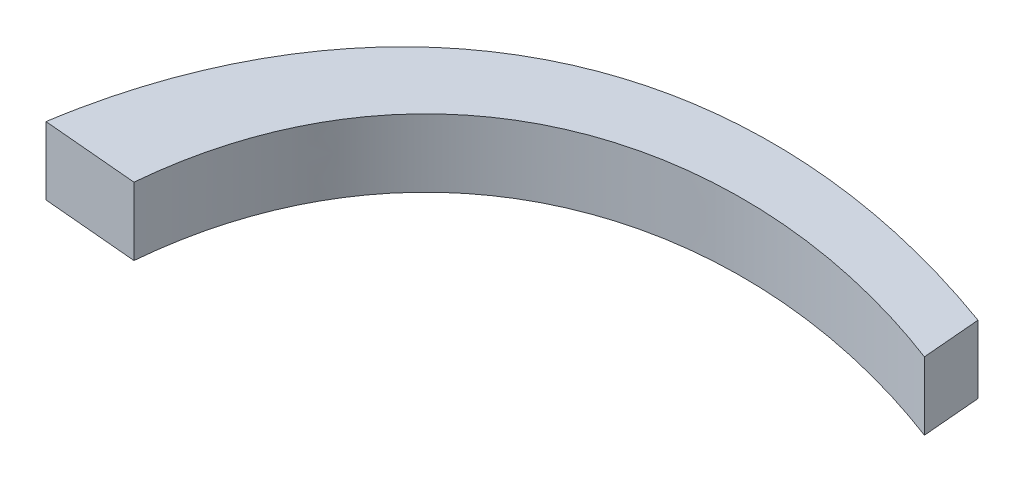
SolidWorks part; units mm, degrees
ref_plane "Front Plane" through (0, 0, 0) normal (0, 0, 1) x (1, 0, 0)
ref_plane "Top Plane" through (0, 0, 0) normal (0, 1, 0) x (1, 0, 0)
ref_plane "Right Plane" through (0, 0, 0) normal (1, 0, 0) x (0, 0, -1)
sketch "Sketch1" plane through (0, 0, 0) normal (0, 1, 0) x (1, 0, 0)
  line L0 (0, 0) -> (-26.9954, 2.3849)
  line L1 (152.9321, 68.2759) -> (151.5408, 84.6576)
  spline S0 degree 3 poles (0, 0) (6.711, 75.965) (73.6865, 98.3324) (152.9321, 68.2759) knots 0 0 0 0 1 1 1 1
  spline S1 degree 3 poles (-26.9954, 2.3849) (-15.1842, 78.2252) (44.207, 123.4901) (151.5408, 84.6576) knots 0 0 0 0 1 1 1 1
  point P2 (159.1679, 85.0426)
  point P8 (-12.2887, 47.4279)
  point P9 (-17.7856, 4.5575)
  dimension "D1" = 200
extrude "Boss-Extrude1" add sketch "Sketch1" along normal blind 19
scale "Scale1" scale about centroid uniform scaling yes scale factor 0.5
